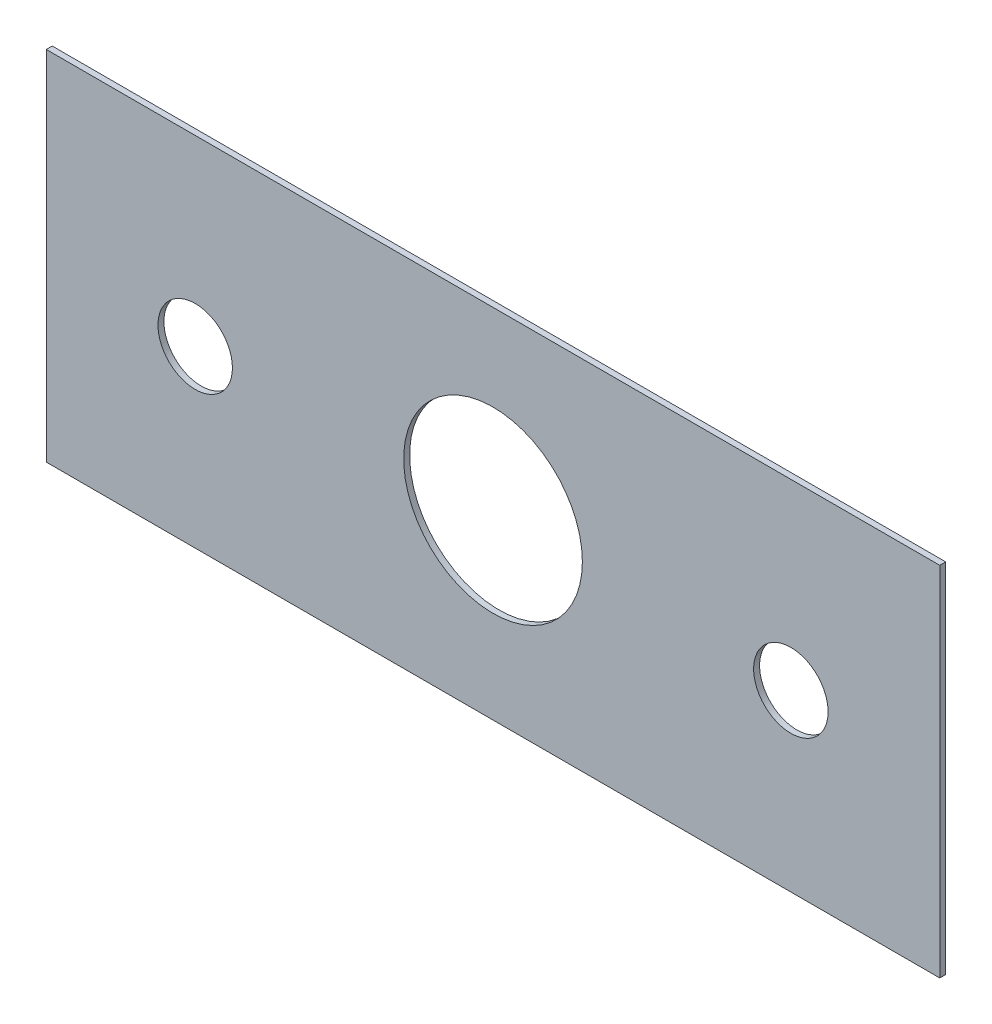
SolidWorks part; units mm, degrees
ref_plane "Front Plane" through (0, 0, 0) normal (0, 0, 1) x (1, 0, 0)
ref_plane "Top Plane" through (0, 0, 0) normal (0, 1, 0) x (1, 0, 0)
ref_plane "Right Plane" through (0, 0, 0) normal (1, 0, 0) x (0, 0, -1)
sketch "Sketch1" plane through (0, 0, 0) normal (0, 0, 1) x (1, 0, 0)
  line L1 (0, 0) -> (-150, 0)
  line L2 (0, 0) -> (0, 60)
  line L3 (0, 60) -> (-150, 60)
  line L4 (-150, 0) -> (-150, 60)
  dimension "D1" = 150
  dimension "D2" = 60
extrude "Boss-Extrude1" add sketch "Sketch1" along normal blind 1
sketch "Sketch2" plane through (0, 0, 1) normal (0, 0, 1) x (1, 0, 0)
  line L0 (-150, 60) -> (-150, 0) construction
  line L1 (0, 0) -> (0, 60) construction
  circle A0 centre (-75, 30.5109) radius 15
  circle A1 centre (-125, 29.3188) radius 6.25
  circle A2 centre (-25, 29.3188) radius 6.25
  point P8 (-150, 30)
  dimension "D2" = 30
  dimension "D3" = 12.5
  dimension "D4" = 12.5
  dimension "D1" = 75
  dimension "D5" = 25
  dimension "D6" = 25
extrude "Cut-Extrude1" cut sketch "Sketch2" against normal through all
